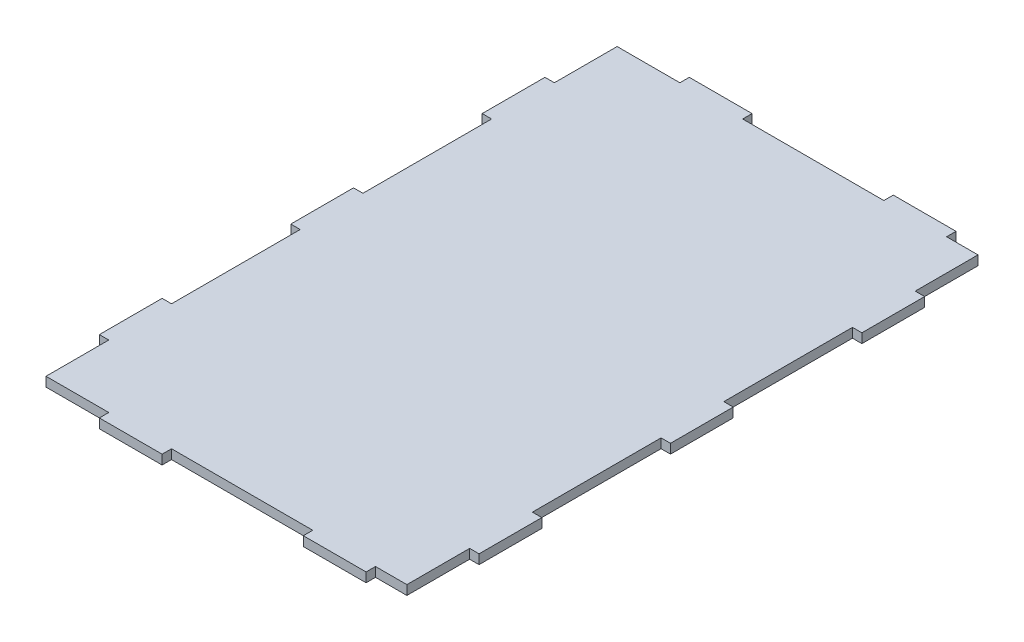
SolidWorks part; units mm, degrees
material "ABS"
ref_plane "Front Plane" through (0, 0, 0) normal (0, 0, 1) x (1, 0, 0)
ref_plane "Top Plane" through (0, 0, 0) normal (0, 1, 0) x (1, 0, 0)
ref_plane "Right Plane" through (0, 0, 0) normal (1, 0, 0) x (0, 0, -1)
sketch "Sketch1" plane through (0, 0, 0) normal (0, 1, 0) x (1, 0, 0)
  line L0 (40, 0) -> (85, 0)
  line L1 (0, 0) -> (20, 0)
  line L2 (0, 0) -> (0, 20)
  line L3 (0, 182) -> (20, 182)
  line L4 (115, 0) -> (115, 20)
  line L6 (20, 0) -> (20, -3)
  line L7 (20, -3) -> (40, -3)
  line L8 (40, 0) -> (40, -3)
  line L10 (85, 0) -> (85, -3)
  line L11 (85, -3) -> (105, -3)
  line L12 (105, 0) -> (105, -3)
  line L13 (0, 40) -> (-3, 40)
  line L15 (0, 20) -> (-3, 20)
  line L16 (-3, 40) -> (-3, 20)
  line L17 (0, 162) -> (-3, 162)
  line L19 (0, 142) -> (-3, 142)
  line L20 (-3, 162) -> (-3, 142)
  line L21 (105, 0) -> (115, 0)
  line L22 (105, 182) -> (115, 182)
  line L23 (105, 182) -> (105, 185)
  line L24 (85, 185) -> (105, 185)
  line L25 (85, 182) -> (85, 185)
  line L26 (40, 182) -> (40, 185)
  line L27 (20, 182) -> (20, 185)
  line L28 (20, 185) -> (40, 185)
  line L29 (40, 182) -> (85, 182)
  line L30 (115, 162) -> (115, 182)
  line L31 (0, 101) -> (-3, 101)
  line L33 (0, 81) -> (-3, 81)
  line L34 (-3, 101) -> (-3, 81)
  line L35 (115, 162) -> (118, 162)
  line L37 (115, 142) -> (118, 142)
  line L38 (118, 162) -> (118, 142)
  line L39 (115, 101) -> (118, 101)
  line L41 (115, 81) -> (118, 81)
  line L42 (118, 101) -> (118, 81)
  line L43 (115, 40) -> (118, 40)
  line L45 (115, 20) -> (118, 20)
  line L46 (118, 40) -> (118, 20)
  line L47 (115, 101) -> (115, 142)
  line L48 (115, 40) -> (115, 81)
  line L49 (0, 162) -> (0, 182)
  line L50 (0, 101) -> (0, 142)
  line L51 (0, 40) -> (0, 81)
  dimension "D1" = 115
  dimension "D2" = 182
  dimension "D3" = 20
  dimension "D4" = 20
  dimension "D5" = 3
  dimension "D6" = 3
  dimension "D7" = 20
  dimension "D8" = 20
  dimension "D9" = 3
  dimension "D10" = 3
  dimension "D11" = 20
  dimension "D12" = 45
  dimension "D13" = 20
  dimension "D14" = 20
  dimension "D15" = 20
  dimension "D16" = 3
  dimension "D17" = 20
  dimension "D18" = 41
  dimension "D19" = 3
  dimension "D20" = 3
  dimension "D21" = 3
  dimension "D22" = 20
  dimension "D23" = 20
  dimension "D24" = 20
  dimension "D25" = 20
  dimension "D26" = 41
  dimension "D27" = 41
  dimension "D28" = 3
  dimension "D29" = 20
  dimension "D30" = 20
  dimension "D31" = 3
  dimension "D32" = 10
  dimension "D33" = 45
  dimension "D34" = 185
  dimension "D35" = 3
extrude "Boss-Extrude1" add sketch "Sketch1" along normal blind 3
